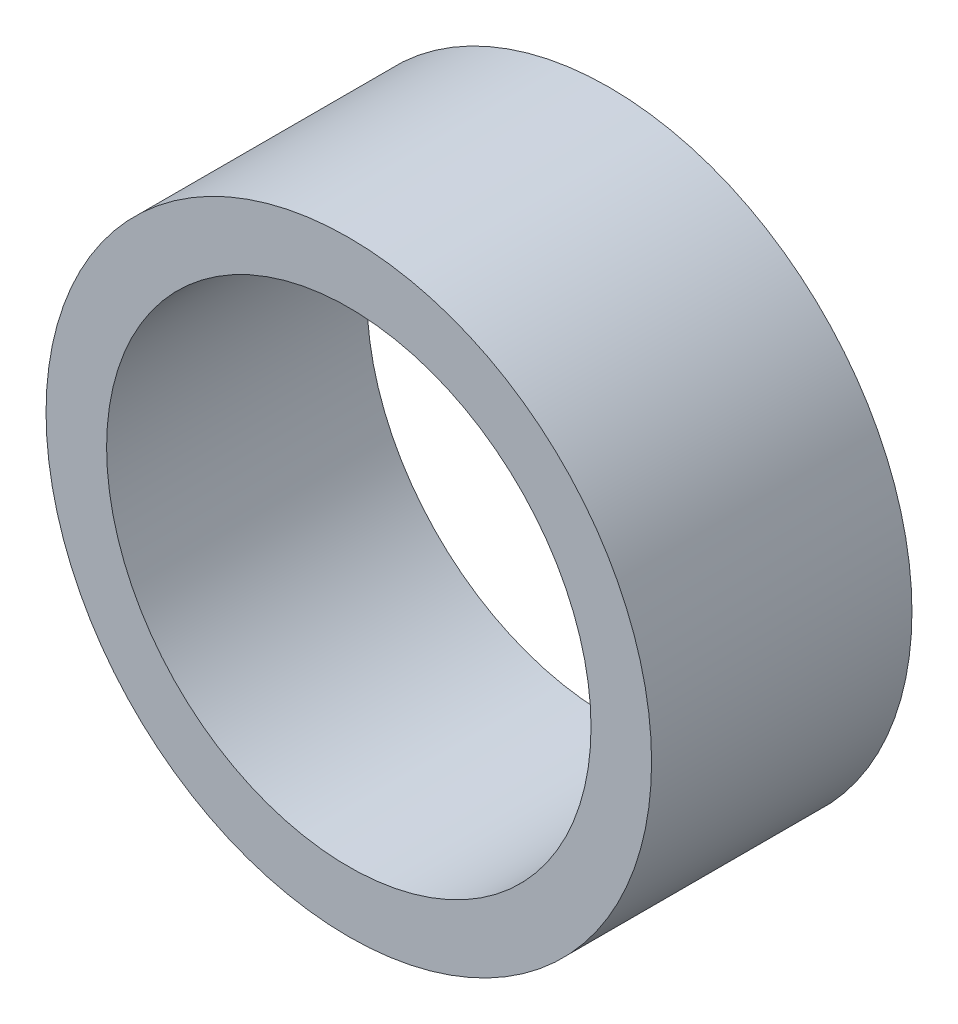
SolidWorks part; units mm, degrees
material "Chêne"
ref_plane "Plan de face" through (0, 0, 0) normal (0, 0, 1) x (1, 0, 0)
ref_plane "Plan de dessus" through (0, 0, 0) normal (0, 1, 0) x (1, 0, 0)
ref_plane "Plan de droite" through (0, 0, 0) normal (1, 0, 0) x (0, 0, -1)
sketch "Esquisse1" plane through (0, 0, 0) normal (0, 0, 1) x (1, 0, 0)
  circle A0 centre (0, 0) radius 12.5
  circle A4 centre (0, 0) radius 10
  point P116 (0, 0)
  point P374 (0, 0)
extrude "Boss.-Extru.1" add sketch "Esquisse1" along normal blind 10.75
